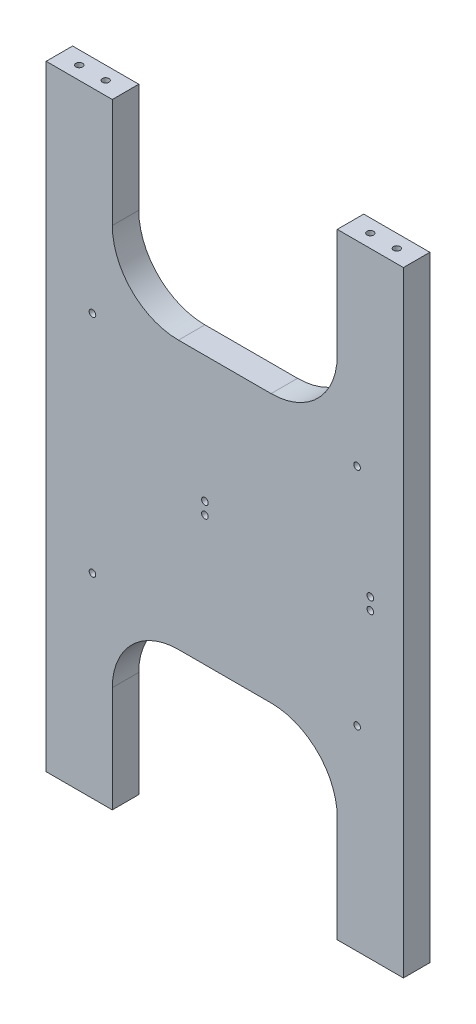
SolidWorks part; units mm, degrees
ref_plane "Ön Düzlem" through (0, 0, 0) normal (0, 0, 1) x (1, 0, 0)
ref_plane "Üst Düzlem" through (0, 0, 0) normal (0, 1, 0) x (1, 0, 0)
ref_plane "Sağ Düzlem" through (0, 0, 0) normal (1, 0, 0) x (0, 0, -1)
sketch "Sketch1" plane through (0, 0, 0) normal (0, 0, 1) x (1, 0, 0)
  line L0 (85, 232.5) -> (135, 232.5)
  line L1 (-135, -232.5) -> (-85, -232.5)
  line L2 (-135, -232.5) -> (-135, 232.5)
  line L3 (-135, 232.5) -> (-85, 232.5)
  line L4 (135, -232.5) -> (135, 232.5)
  line L5 (-135, -232.5) -> (135, 232.5) construction
  line L6 (-135, 232.5) -> (135, -232.5) construction
  line L8 (-85, 232.5) -> (-85, 150)
  line L9 (-35, 100) -> (35, 100)
  line L10 (85, 232.5) -> (85, 150)
  line L12 (85, -232.5) -> (85, -152.5)
  line L13 (-85, -232.5) -> (-85, -152.5)
  line L14 (-35, -102.5) -> (35, -102.5)
  line L15 (85, -232.5) -> (135, -232.5)
  arc A0 (35, 100) -> (85, 150) centre (35, 150) ccw
  arc A1 (-85, 150) -> (-35, 100) centre (-35, 150) ccw
  arc A2 (-85, -152.5) -> (-35, -102.5) centre (-35, -152.5) cw
  arc A3 (35, -102.5) -> (85, -152.5) centre (35, -152.5) cw
  point P0 (0, 0)
  dimension "D5" = 50
  dimension "D1" = 270
  dimension "D2" = 465
  dimension "D3" = 50
  dimension "D4" = 50
  dimension "D6" = 100
extrude "Boss-Extrude1" add sketch "Sketch1" along normal blind 20
sketch "Sketch2" plane through (0, -232.5, 0) normal (0, -1, 0) x (1, 0, 0)
  line L0 (0, 0) -> (0, 33.7987) construction
  line L1 (-135, 10) -> (-85, 10) construction
  line L2 (-135, 20) -> (-135, 0) construction
  line L3 (-85, 20) -> (-85, 0) construction
  circle A0 centre (-120, 10) radius 2.5
  circle A1 centre (-100, 10) radius 2.5
  circle A2 centre (100, 10) radius 2.5
  circle A3 centre (120, 10) radius 2.5
  dimension "D1" = 5
  dimension "D2" = 5
  dimension "D3" = 15
  dimension "D4" = 20
extrude "Cut-Extrude1" cut sketch "Sketch2" against normal blind 20
mirror "Mirror1" about plane through (0, 0, 0) normal (0, 1, 0) of "Cut-Extrude1"
sketch "Sketch3" plane through (0, 0, 20) normal (0, 0, 1) x (1, 0, 0)
  line L0 (0, 0) -> (0, 85) construction
  line L1 (0, 85) -> (100, 85) construction
  line L2 (0, 0) -> (27.9507, 0) construction
  circle A0 centre (100, 85) radius 2.5
  circle A1 centre (100, -85) radius 2.5
  circle A2 centre (-100, 85) radius 2.5
  circle A3 centre (-100, -85) radius 2.5
  dimension "D3" = 5
  dimension "D1" = 85
  dimension "D2" = 100
extrude "Cut-Extrude2" cut sketch "Sketch3" against normal blind 20
sketch "Sketch4" plane through (0, 0, 0) normal (0, 0, -1) x (-1, 0, 0)
  line L0 (-135, 0) -> (135, 0) construction
  line L1 (-135, -232.5) -> (-135, 232.5) construction
  line L2 (135, 232.5) -> (135, -232.5) construction
  line L3 (0, 0) -> (0, 53.5471) construction
  line L4 (-110, 0) -> (-110, 4.5) construction
  line L5 (15, 0) -> (15, 4.5) construction
  circle A0 centre (-110, 4.5) radius 2.5
  circle A1 centre (-110, -4.5) radius 2.5
  circle A2 centre (15, 4.5) radius 2.5
  circle A3 centre (15, -4.5) radius 2.5
  dimension "D1" = 5
  dimension "D4" = 5
  dimension "D2" = 4.5
  dimension "D3" = 25
  dimension "D5" = 4.5
  dimension "D6" = 120
extrude "Cut-Extrude3" cut sketch "Sketch4" against normal up to surface (20 mm away) up to face at (97.5, -85, 20)
sketch "Sketch5" plane through (0, 0, 0) normal (0, 0, -1) x (-1, 0, 0)
  line L0 (-110, 4.5) -> (15, 4.5) construction
  line L1 (15, 4.5) -> (15, -4.5) construction
  line L2 (-47.5, 4.5) -> (-47.5, -8.8724) construction
  circle A0 centre (-110, 4.5) radius 4
  circle A1 centre (-110, -4.5) radius 4
  circle A2 centre (15, 4.5) radius 4
  circle A3 centre (15, -4.5) radius 4
  dimension "D1" = 8
  dimension "D2" = 8
extrude "Cut-Extrude4" cut sketch "Sketch5" against normal blind 5
